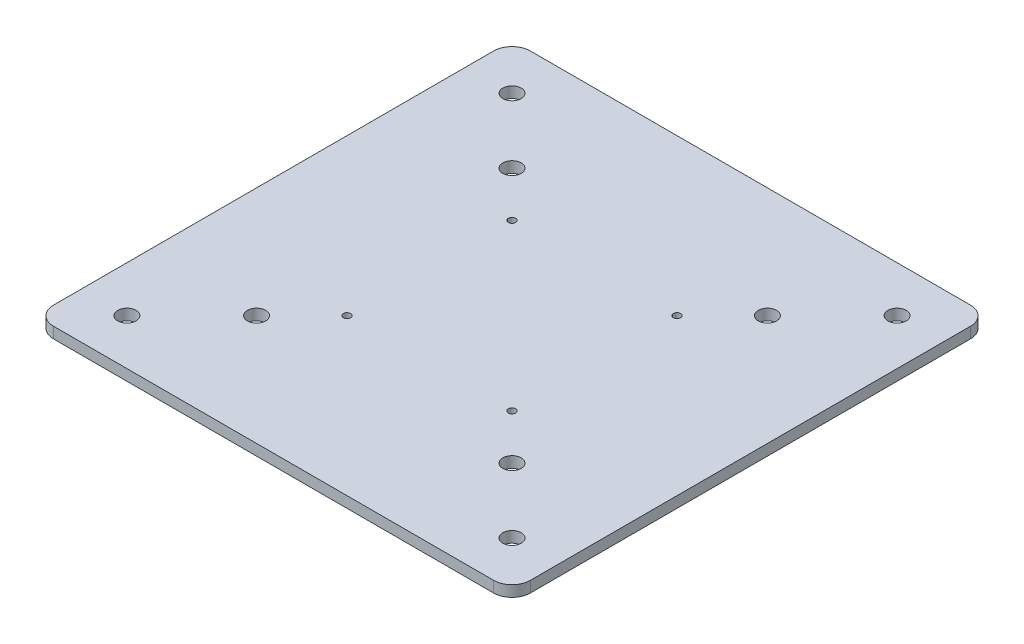
SolidWorks part; units mm, degrees
ref_plane "Front Plane" through (0, 0, 0) normal (0, 0, 1) x (1, 0, 0)
ref_plane "Top Plane" through (0, 0, 0) normal (0, 1, 0) x (1, 0, 0)
ref_plane "Right Plane" through (0, 0, 0) normal (1, 0, 0) x (0, 0, -1)
sketch "Sketch1" plane through (0, 0, 0) normal (0, 1, 0) x (1, 0, 0)
  line L0 (-52.5, 52.5) -> (52.5, 52.5) construction
  line L1 (-65, 65) -> (65, 65)
  line L2 (-65, 65) -> (-65, -65)
  line L3 (-65, -65) -> (65, -65)
  line L4 (65, 65) -> (65, -65)
  line L5 (-65, 65) -> (65, -65) construction
  line L6 (-65, -65) -> (65, 65) construction
  line L7 (-99.0677, 0) -> (99.0677, 0) construction
  line L8 (-22.5, 22.5) -> (22.5, 22.5) construction
  circle A0 centre (-52.5, 52.5) radius 2.5
  circle A1 centre (-34.8223, 34.8223) radius 2.5
  circle A2 centre (52.5, 52.5) radius 2.5
  circle A3 centre (34.8223, 34.8223) radius 2.5
  circle A4 centre (52.5, -52.5) radius 2.5
  circle A5 centre (34.8223, -34.8223) radius 2.5
  circle A6 centre (-34.8223, -34.8223) radius 2.5
  circle A7 centre (-52.5, -52.5) radius 2.5
  circle A8 centre (-22.5, 22.5) radius 1
  circle A9 centre (22.5, 22.5) radius 1
  circle A10 centre (22.5, -22.5) radius 1
  circle A11 centre (-22.5, -22.5) radius 1
  point P0 (0, 0)
  point P17 (0, 0)
  dimension "D3" = 5
  dimension "D6" = 2
  dimension "D7" = 2
  dimension "D1" = 130
  dimension "D2" = 25
  dimension "D4" = 25
  dimension "D5" = 105
  dimension "D8" = 45
extrude "Boss-Extrude1" add sketch "Sketch1" along normal blind 3
fillet "Fillet1" radius 5 4 edges at (-65, 1.5, 65) (65, 1.5, 65) (-65, 1.5, -65) (65, 1.5, -65)
